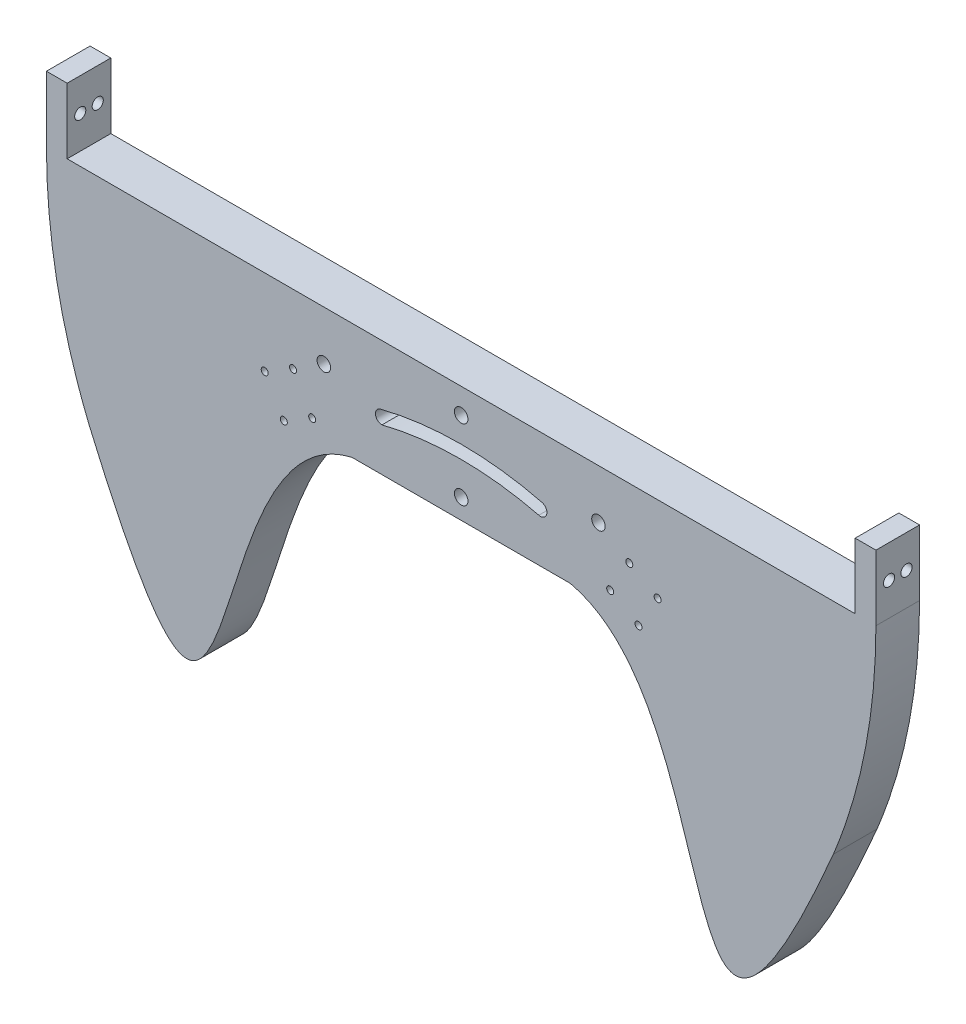
SolidWorks part; units mm, degrees
ref_plane "前视基准面" through (0, 0, 0) normal (0, 0, 1) x (1, 0, 0)
ref_plane "上视基准面" through (0, 0, 0) normal (0, 1, 0) x (1, 0, 0)
ref_plane "右视基准面" through (0, 0, 0) normal (1, 0, 0) x (0, 0, -1)
other "Configuration Table"
sketch "草图1" plane through (0, 0, 0) normal (0, 0, 1) x (1, 0, 0)
  line L0 (-49.7234, 34.8249) -> (50.2766, 34.8249)
  line L1 (-189.7234, 88.03) -> (190.2766, 88.03)
  circle A0 centre (-62.6275, 65.4114) radius 3.1
  circle A1 centre (-76.733, 56.4146) radius 1.6
  circle A2 centre (-89.7234, 48.9146) radius 1.6
  circle A3 centre (-67.983, 41.2591) radius 1.6
  circle A4 centre (-80.9734, 33.7591) radius 1.6
  circle A5 centre (0.2766, 76.53) radius 3.1
  circle A6 centre (0.2766, 44.03) radius 3.1
  circle A7 centre (63.1807, 65.4114) radius 3.1
  circle A8 centre (77.2862, 56.4146) radius 1.6
  circle A9 centre (90.2766, 48.9146) radius 1.6
  circle A10 centre (81.5266, 33.7591) radius 1.6
  circle A11 centre (68.5362, 41.2591) radius 1.6
  arc A12 (-36.7375, 60.4853) -> (37.2906, 60.4853) centre (0.2766, -87.232) cw
  arc A13 (-36.0117, 54.5744) -> (-36.7375, 60.4853) centre (-36.0082, 57.5748) cw
  arc A14 (37.2906, 60.4853) -> (35.8391, 54.6635) centre (36.5615, 57.5752) cw
  arc A15 (-36.0117, 54.5744) -> (35.8391, 54.6635) centre (0.0924, -89.4283) cw
  arc A16 (170.7876, -12.3602) -> (-170.2344, -12.3602) centre (0.2766, -106.97) ccw
  spline S0 degree 3 poles (-49.7234, 34.8249) (-124.0132, 17.8433) (-95.0021, -188.0794) (-170.2344, -12.3602) knots 0 0 0 0 1 1 1 1
  spline S1 degree 3 poles (50.2766, 34.8249) (124.5664, 17.8433) (95.5553, -188.0794) (170.7876, -12.3602) knots 0 0 0 0 1 1 1 1
  spline S2 degree 2 poles (-189.7234, 88.03) (-189.6067, 29.2631) (-165.9555, -22.1978) knots 0 0 0 1 1 1
  spline S3 degree 2 poles (190.2766, 88.03) (190.1599, 29.2631) (166.5087, -22.1978) knots 0 0 0 1 1 1
  point P0 (0, 0)
  point P10 (0.2766, 88.03)
  point P11 (0.2766, 88.03)
  dimension "D1" = 195
  dimension "D2" = 6.2
  dimension "D3" = 6.2
  dimension "D4" = 6.2
  dimension "D5" = 22.6187
extrude "凸台-拉伸1" add sketch "草图1" along normal mid plane 20 contours L0 S1 A16 S0 A0 A1 A2 A3 A4 A5 A6 A7 A8 A9 A10 A11 A15 A13 A12 A14 | L1 S2 A16 | S3 L1 A16
sketch "草图7" plane through (0, 88.03, 0) normal (0, 1, 0) x (1, 0, 0)
  line L0 (0, 0) -> (190.2766, 0) construction
  line L2 (0, 0) -> (0, 101.6503) construction
  line L3 (-180.2234, 10) -> (-180.2234, -10)
  line L4 (-189.7234, 10) -> (190.2766, 10) construction
  line L5 (-189.7234, -10) -> (190.2766, -10) construction
  line L6 (180.7766, 10) -> (180.7766, -10)
  line L7 (-189.7234, -10) -> (-189.7234, 10) construction
  line L8 (190.2766, -10) -> (190.2766, 10) construction
  line L9 (-189.7234, -10) -> (-189.7234, 10)
  line L10 (-189.7234, 10) -> (-180.2234, 10)
  line L11 (-189.7234, -10) -> (-180.2234, -10)
  line L12 (180.7766, -10) -> (190.2766, -10)
  line L13 (190.2766, -10) -> (190.2766, 10)
  line L14 (190.2766, 10) -> (180.7766, 10)
  dimension "D1" = 9.5
  dimension "D2" = 9.5
extrude "凸台-拉伸2" add sketch "草图7" along normal blind 30
sketch "草图8" plane through (-189.7234, 0, 0) normal (-1, 0, 0) x (0, 0, 1)
  line L0 (0, 0) -> (0, 123.7567) construction
  line L1 (-10, 118.03) -> (10, 118.03) construction
  circle A0 centre (-4, 103.03) radius 2.55
  circle A1 centre (4, 103.03) radius 2.55
  dimension "D1" = 5.1
  dimension "D2" = 5.1
  dimension "D3" = 8
  dimension "D4" = 4
  dimension "D5" = 15
  dimension "D6" = 4
extrude "切除-拉伸1" cut sketch "草图8" against normal through all and the other way through all
